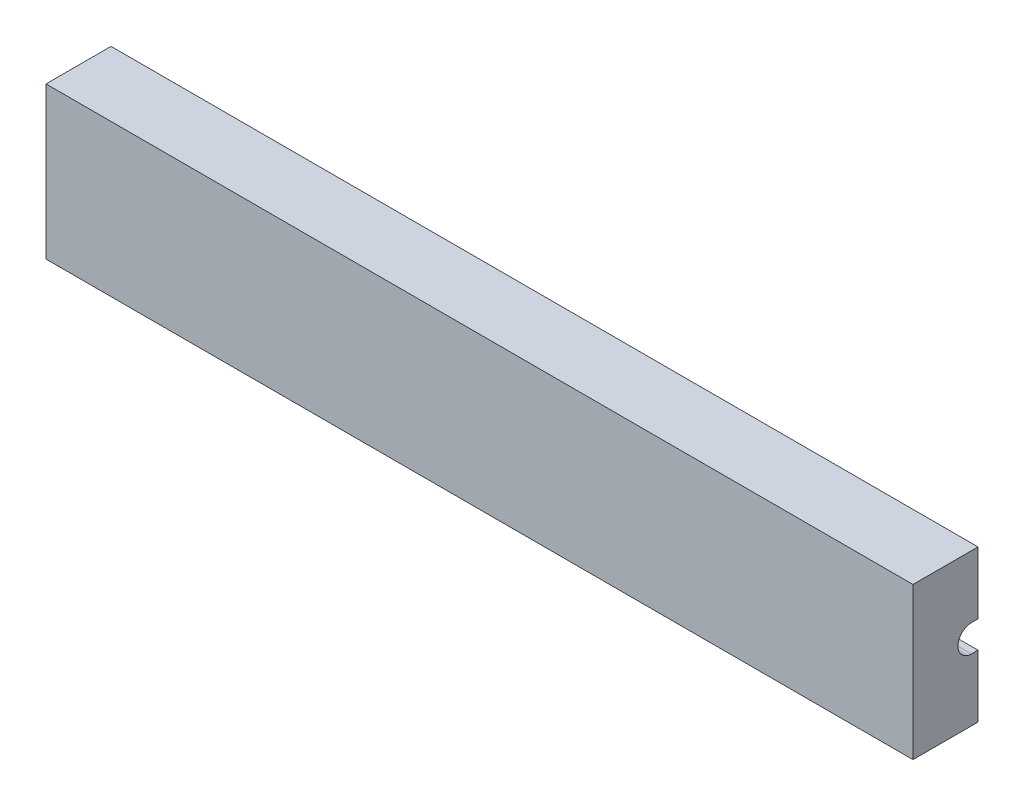
SolidWorks part; units mm, degrees
ref_plane "Front Plane" through (0, 0, 0) normal (0, 0, 1) x (1, 0, 0)
ref_plane "Top Plane" through (0, 0, 0) normal (0, 1, 0) x (1, 0, 0)
ref_plane "Right Plane" through (0, 0, 0) normal (1, 0, 0) x (0, 0, -1)
ref_plane "Plane1" through (190.6451, 0, 0) normal (1, 0, 0) x (0, 0, -1)
sketch "Sketch1" plane through (190.6451, 0, 0) normal (1, 0, 0) x (0, 0, -1)
  line L0 (-246.9709, 208.1635) -> (-246.9709, 205.1635) construction
  line L1 (-240.9709, 205.1635) -> (-240.9709, 208.1635) construction
  line L2 (-240.9709, 208.1635) -> (-246.9709, 208.1635) construction
  line L3 (-240.9709, 199.9135) -> (-241.5709, 199.9135) construction
  line L4 (-241.5709, 202.4135) -> (-240.9709, 202.4135) construction
  line L5 (-240.9709, 202.4135) -> (-240.9709, 205.1635) construction
  line L6 (-246.9709, 205.1635) -> (-246.9709, 197.1635) construction
  line L7 (-240.9709, 197.1635) -> (-240.9709, 199.9135) construction
  line L8 (-246.9709, 197.1635) -> (-246.9709, 194.1635) construction
  line L9 (-246.9709, 194.1635) -> (-240.9709, 194.1635) construction
  line L10 (-240.9709, 194.1635) -> (-240.9709, 197.1635) construction
  line L11 (-246.9709, 208.1635) -> (-246.9709, 205.1635)
  line L12 (-240.9709, 205.1635) -> (-240.9709, 208.1635)
  line L13 (-240.9709, 208.1635) -> (-246.9709, 208.1635)
  line L14 (-240.9709, 199.9135) -> (-241.5709, 199.9135)
  line L15 (-241.5709, 202.4135) -> (-240.9709, 202.4135)
  line L16 (-240.9709, 202.4135) -> (-240.9709, 205.1635)
  line L17 (-246.9709, 205.1635) -> (-246.9709, 197.1635)
  line L18 (-240.9709, 197.1635) -> (-240.9709, 199.9135)
  line L19 (-246.9709, 197.1635) -> (-246.9709, 194.1635)
  line L20 (-246.9709, 194.1635) -> (-240.9709, 194.1635)
  line L21 (-240.9709, 194.1635) -> (-240.9709, 197.1635)
  arc A0 (-241.5709, 202.4135) -> (-241.5709, 199.9135) centre (-241.5709, 201.1635) ccw construction
  arc A1 (-241.5709, 202.4135) -> (-241.5709, 199.9135) centre (-241.5709, 201.1635) ccw
extrude "Boss-Extrude1" add sketch "Sketch1" along normal blind 60 and the other way blind 20
